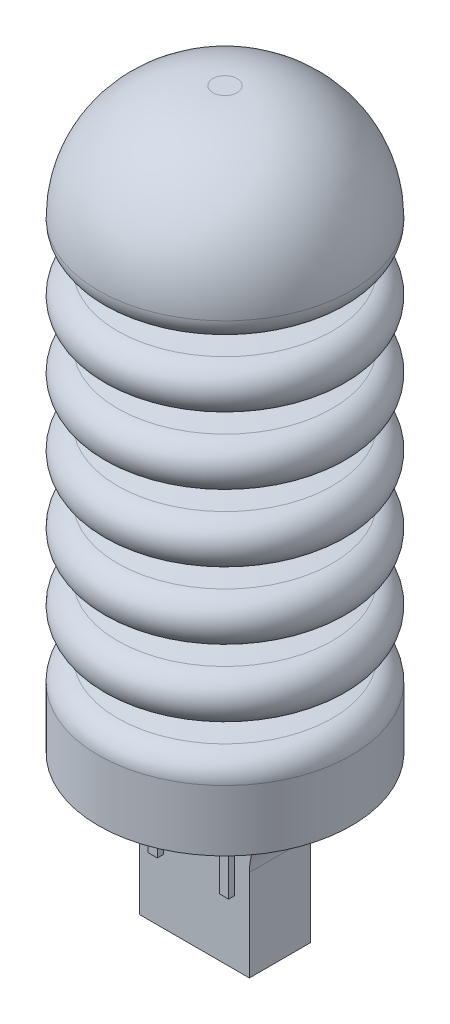
SolidWorks part; units mm, degrees
ref_plane "Front Plane" through (0, 0, 0) normal (0, 0, 1) x (1, 0, 0)
ref_plane "Top Plane" through (0, 0, 0) normal (0, 1, 0) x (1, 0, 0)
ref_plane "Right Plane" through (0, 0, 0) normal (1, 0, 0) x (0, 0, -1)
sketch "Sketch1" plane through (0, 0, 0) normal (1, 0, 0) x (0, 0, -1)
  line L0 (-9.6168, 62.5511) -> (-3.2517, 61.4898)
  line L3 (6, 85) -> (8, 85)
  line L4 (8, 83) -> (8, 85)
  line L5 (-10.7758, 0.25) -> (-12.75, 0.25)
  line L6 (-9.6168, 58.949) -> (-3.2517, 60.0102)
  line L7 (-2.9428, 52.4658) -> (-9.2826, 53.4748)
  line L9 (6, 83) -> (8, 83)
  line L10 (8, 83) -> (8, 85)
  line L11 (8, 83) -> (8, 0) construction
  line L13 (-9.6168, 40.5511) -> (-3.2517, 39.4898)
  line L14 (-9.6168, 51.5511) -> (-3.2517, 50.4898)
  line L15 (-9.6167, 47.949) -> (-3.2517, 49.0102)
  line L16 (-9.6167, 36.949) -> (-3.2517, 38.0102)
  line L17 (-9.6168, 29.5511) -> (-3.2517, 28.4898)
  line L18 (-9.6168, 18.5511) -> (-3.2517, 17.4898)
  line L19 (-9.6167, 14.949) -> (-3.2517, 16.0102)
  line L20 (-9.6168, 7.5511) -> (-3.2517, 6.4898)
  line L21 (-9.6168, 3.949) -> (-3.2517, 5.0102)
  line L22 (-9.2878, 64.5239) -> (-2.9227, 63.4626)
  line L23 (-9.2676, 46.086) -> (-2.9674, 47.0304)
  line L24 (-9.2678, 42.4141) -> (-2.9227, 41.4626)
  line L25 (-9.2826, 35.0031) -> (-2.9336, 36.0357)
  line L26 (-9.2826, 31.4969) -> (-2.9336, 30.4643)
  line L27 (-9.6167, 25.949) -> (-3.2517, 27.0102)
  line L28 (-9.2826, 24.0031) -> (-2.9336, 25.0357)
  line L29 (-9.2826, 20.4969) -> (-2.9336, 19.4643)
  line L30 (-9.2826, 13.0031) -> (-2.9336, 14.0357)
  line L31 (-9.2826, 9.4969) -> (-2.9336, 8.4643)
  line L32 (-9.2825, 2.0031) -> (-2.9336, 3.0357)
  line L33 (-9.2825, 57.0252) -> (-2.9428, 58.0342)
  arc A0 (6, 85) -> (-12.75, 66.25) centre (6, 66.25) ccw
  arc A2 (-12.75, 66.25) -> (-9.6168, 62.5511) centre (-9, 66.25) ccw
  arc A4 (-9.6167, 47.949) -> (-9.6168, 40.5511) centre (-9, 44.25) ccw
  arc A5 (-9.6167, 36.949) -> (-9.6168, 29.5511) centre (-9, 33.25) ccw
  arc A6 (-9.6167, 25.949) -> (-9.6168, 18.5511) centre (-9, 22.25) ccw
  arc A7 (-9.6167, 14.949) -> (-9.6168, 7.5511) centre (-9, 11.25) ccw
  arc A8 (-2.9428, 58.0342) -> (-2.9227, 63.4626) centre (-3.375, 60.75) ccw
  arc A9 (-2.9674, 47.0304) -> (-2.9428, 52.4658) centre (-3.375, 49.75) ccw
  arc A10 (-2.9336, 36.0357) -> (-2.9227, 41.4626) centre (-3.375, 38.75) ccw
  arc A11 (-2.9336, 25.0357) -> (-2.9336, 30.4643) centre (-3.375, 27.75) ccw
  arc A12 (-2.9336, 14.0357) -> (-2.9336, 19.4643) centre (-3.375, 16.75) ccw
  arc A14 (-9.6167, 3.949) -> (-12.75, 0.25) centre (-9, 0.25) ccw
  arc A15 (-2.9336, 3.0357) -> (-2.9336, 8.4643) centre (-3.375, 5.75) ccw
  arc A16 (-10.75, 66.25) -> (-9.2878, 64.5239) centre (-9, 66.25) ccw
  arc A17 (-3.2517, 60.0102) -> (-3.2517, 61.4898) centre (-3.375, 60.75) ccw
  arc A18 (-9.2825, 57.0252) -> (-9.2826, 53.4748) centre (-9, 55.25) ccw
  arc A19 (-3.2517, 49.0102) -> (-3.2517, 50.4898) centre (-3.375, 49.75) ccw
  arc A20 (-9.2676, 46.086) -> (-9.2678, 42.4141) centre (-9, 44.25) ccw
  arc A21 (-3.2517, 38.0102) -> (-3.2517, 39.4898) centre (-3.375, 38.75) ccw
  arc A22 (-9.2826, 35.0031) -> (-9.2826, 31.4969) centre (-9, 33.25) ccw
  arc A23 (-3.2517, 27.0102) -> (-3.2517, 28.4898) centre (-3.375, 27.75) ccw
  arc A24 (-9.2826, 24.0031) -> (-9.2826, 20.4969) centre (-9, 22.25) ccw
  arc A25 (-3.2517, 16.0102) -> (-3.2517, 17.4898) centre (-3.375, 16.75) ccw
  arc A26 (-9.2826, 13.0031) -> (-9.2826, 9.4969) centre (-9, 11.25) ccw
  arc A27 (-3.2517, 5.0102) -> (-3.2517, 6.4898) centre (-3.375, 5.75) ccw
  arc A28 (-9.2825, 2.0031) -> (-10.7758, 0.25) centre (-9, 0.25) ccw
  arc A29 (6, 83) -> (-10.75, 66.25) centre (6, 66.25) ccw
  arc A32 (-9.6167, 58.949) -> (-9.6168, 51.5511) centre (-9, 55.25) ccw
  dimension "D4" = 18.75
  dimension "D6" = 7.5
  dimension "D11" = 11
  dimension "D13" = 5.5
  dimension "D21" = 2
  dimension "D22" = 2
  dimension "D7" = 11
  dimension "D8" = 11
  dimension "D9" = 11
  dimension "D10" = 11
  dimension "D12" = 11
  dimension "D15" = 11
  dimension "D16" = 11
  dimension "D17" = 11
  dimension "D18" = 11
  dimension "D19" = 11
revolve "Revolve2" add sketch "Sketch1" angle 360 about L11
sketch "Sketch4" plane through (0, 0.25, 0) normal (0, -1, 0) x (1, 0, 0)
  line L2 (0.9886, -28.7265) -> (0.9886, 12.7265)
  line L4 (-0.9886, -28.7265) -> (-0.9886, 12.7265)
  line L5 (0.9886, -28.7265) -> (-0.9886, 12.7265) construction
  line L6 (0.9886, 12.7265) -> (-0.9886, -28.7265) construction
  arc A0 (0.9886, 12.7265) -> (-0.9886, 12.7265) centre (0, -8) ccw
  arc A1 (-0.9886, -28.7265) -> (0.9886, -28.7265) centre (0, -8) ccw
  dimension "D1" = 1.9771
extrude "Boss-Extrude2" add sketch "Sketch4" against normal up to next
sketch "Sketch2" plane through (0, 0.25, 0) normal (0, -1, 0) x (1, 0, 0)
  circle A0 centre (0, -8) radius 20.75
extrude "Boss-Extrude1" add sketch "Sketch2" along normal blind 10
sketch "Sketch5" plane through (0, -9.75, 0) normal (0, -1, 0) x (1, 0, 0)
  circle A0 centre (-4, -8) radius 2.05
  circle A1 centre (4, -8) radius 2.05
  dimension "D1" = 4.1
  dimension "D2" = 4.1
  dimension "D3" = 8
extrude "Cut-Extrude1" cut sketch "Sketch5" against normal blind 10
sketch "Sketch6" plane through (0, -9.75, 0) normal (0, -1, 0) x (1, 0, 0)
  line L1 (9, -3) -> (-9, -3)
  line L2 (9, -3) -> (9, -13)
  line L3 (9, -13) -> (-9, -13)
  line L4 (-9, -3) -> (-9, -13)
  line L5 (9, -3) -> (-9, -13) construction
  line L6 (9, -13) -> (-9, -3) construction
  circle A0 centre (-4, -8) radius 2.05
  circle A1 centre (4, -8) radius 2.05
  point P0 (0, -8)
  dimension "D1" = 18
  dimension "D2" = 10
extrude "Boss-Extrude3" add sketch "Sketch6" along normal blind 25
fillet "Fillet1" radius 10 2 edges at (9, -9.75, -8) (-9, -9.75, -8)
sketch "Sketch7" plane through (0, 0, -3) normal (0, 0, 1) x (1, 0, 0)
  line L0 (19, -9.75) -> (-19, -9.75) construction
  line L1 (-6.6, -9.75) -> (-5.1, -9.75)
  line L2 (-6.6, -9.75) -> (-6.6, -24.25)
  line L3 (-6.6, -24.25) -> (-5.1, -24.25)
  line L4 (-5.1, -9.75) -> (-5.1, -24.25)
  line L6 (6.6, -9.75) -> (5.1, -9.75)
  line L7 (6.6, -9.75) -> (6.6, -24.25)
  line L8 (6.6, -24.25) -> (5.1, -24.25)
  line L9 (5.1, -9.75) -> (5.1, -24.25)
  dimension "D1" = 10.2
  dimension "D2" = 5.1
  dimension "D3" = 14.5
  dimension "D4" = 14.5
  dimension "D5" = 1.5
  dimension "D6" = 1.5
extrude "Boss-Extrude4" add sketch "Sketch7" along normal blind 1
